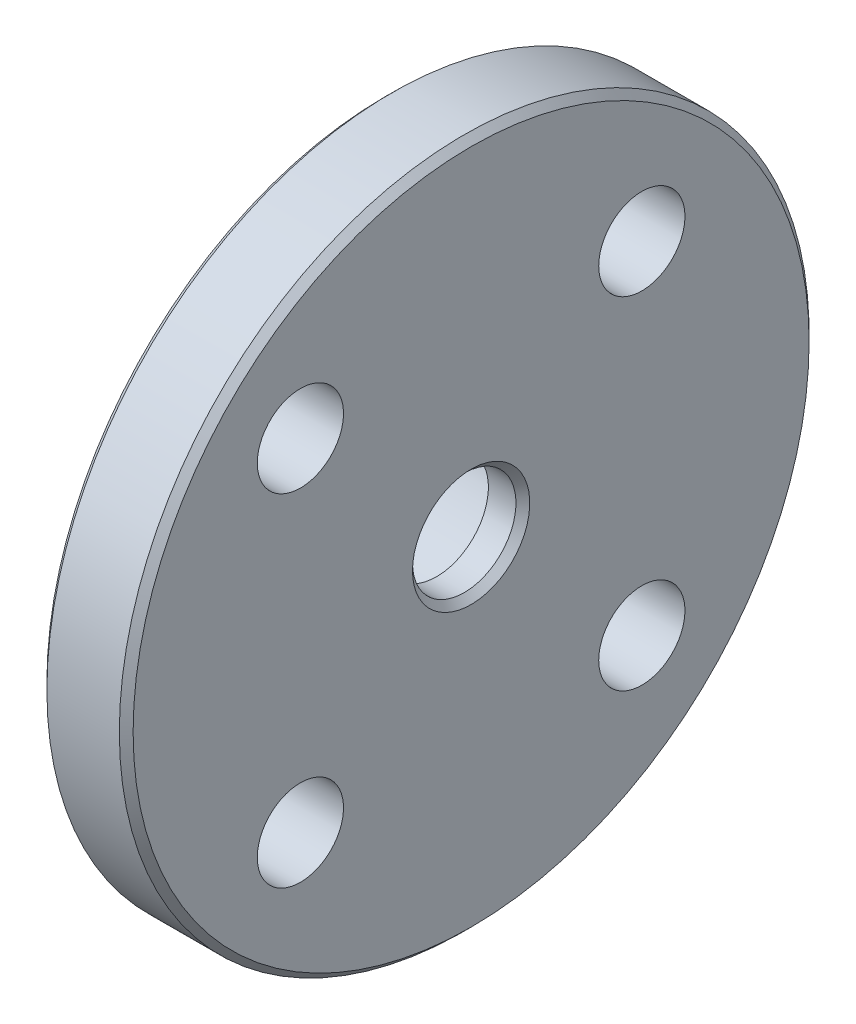
SolidWorks part; units mm, degrees
ref_plane "前视基准面" through (0, 0, 0) normal (0, 0, 1) x (1, 0, 0)
ref_plane "上视基准面" through (0, 0, 0) normal (0, 1, 0) x (1, 0, 0)
ref_plane "右视基准面" through (0, 0, 0) normal (1, 0, 0) x (0, 0, -1)
sketch "草图2" plane through (0, 0, 0) normal (0, 0, 1) x (1, 0, 0)
  line L0 (0, 3) -> (0, 4.5)
  line L1 (0, 4.5) -> (2, 4.5)
  line L2 (2, 4.5) -> (2, 10)
  line L3 (2, 10) -> (4.5, 10)
  line L4 (4.5, 10) -> (4.5, 1.5)
  line L5 (4.5, 1.5) -> (3.5, 1.5)
  line L6 (3.5, 1.5) -> (3.5, 3)
  line L7 (3.5, 3) -> (0, 3)
  line L8 (0, 0) -> (5.26, 0) construction
  dimension "D1" = 1
  dimension "D2" = 3.5
  dimension "D3" = 2.5
  dimension "D4" = 20
  dimension "D5" = 9
  dimension "D6" = 6
  dimension "D7" = 3
revolve "旋转1" add sketch "草图2" angle 360 about L8
sketch "草图3" plane through (2, 0, 0) normal (-1, 0, 0) x (0, 0, 1)
  line L0 (0, 0) -> (10, 0) construction
  line L1 (0, 0) -> (7.0711, 7.0711) construction
  circle A0 centre (0, 0) radius 10 construction
  circle A1 centre (4.9497, 4.9497) radius 1.25
  circle A2 centre (4.9497, -4.9497) radius 1.25
  circle A3 centre (-4.9497, -4.9497) radius 1.25
  circle A4 centre (-4.9497, 4.9497) radius 1.25
  point P18 (0, 0)
  dimension "D2" = 2.5
  dimension "D3" = 7
  dimension "D1" = 45
  dimension "D4" = 4
extrude "切除-拉伸1" cut sketch "草图3" against normal through all
chamfer "倒角1" distance 0.2 angle 45 4 edges at (4.5, 0, 1.5) (4.5, 0, 10) (2, 0, 10) (0, 0, 4.5)
move or copy body "实体-移动/复制1" [suppressed] bodies to move or copy 107
move or copy body "实体-移动/复制2" [suppressed] bodies to move or copy 108 parameters "D1"=0, "D2"=0, "D3"=0
move or copy body "实体-移动/复制3" [suppressed] bodies to move or copy 109 parameters "D1"=0, "D2"=0, "D3"=0
